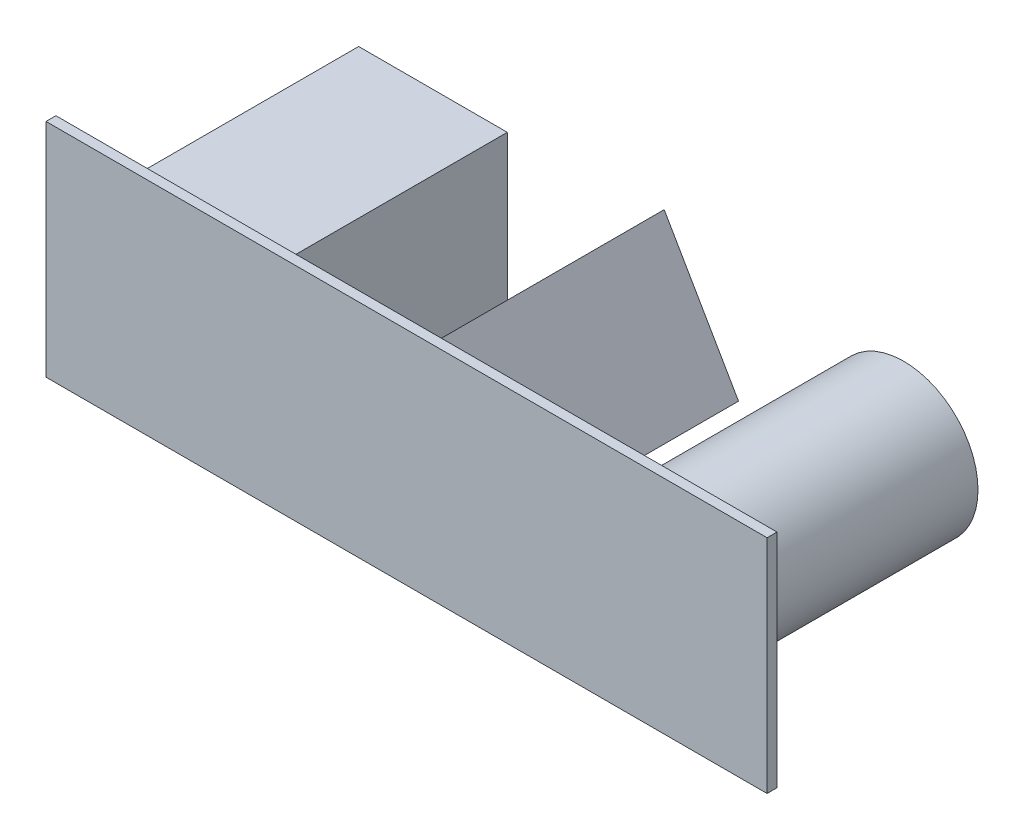
SolidWorks part; units mm, degrees
ref_plane "Front Plane" through (0, 0, 0) normal (0, 0, 1) x (1, 0, 0)
ref_plane "Top Plane" through (0, 0, 0) normal (0, 1, 0) x (1, 0, 0)
ref_plane "Right Plane" through (0, 0, 0) normal (1, 0, 0) x (0, 0, -1)
sketch "Sketch1" plane through (0, 0, 0) normal (0, 0, 1) x (1, 0, 0)
  line L0 (-122.5, 0) -> (122.5, 0) construction
  line L1 (-122.5, 60) -> (122.5, 60)
  line L2 (-122.5, 60) -> (-122.5, -60)
  line L3 (-122.5, -60) -> (122.5, -60)
  line L4 (122.5, 60) -> (122.5, -60)
  line L5 (0, 60) -> (0, -60) construction
  line L6 (-22.5, -12.9904) -> (0, 25.9808)
  line L7 (-92.5, 22.5) -> (-47.5, 22.5)
  line L8 (-92.5, 22.5) -> (-92.5, -22.5)
  line L9 (-92.5, -22.5) -> (-47.5, -22.5)
  line L10 (-47.5, 22.5) -> (-47.5, -22.5)
  line L11 (-92.5, 22.5) -> (-47.5, -22.5) construction
  line L12 (-92.5, -22.5) -> (-47.5, 22.5) construction
  line L14 (-1.3522, 0) -> (0, -1.3522)
  line L18 (0, 25.9808) -> (22.5, -12.9904)
  line L19 (22.5, -12.9904) -> (-22.5, -12.9904)
  line L20 (-22.5, -12.9904) -> (11.25, 6.4952) construction
  line L21 (22.5, -12.9904) -> (-11.25, 6.4952) construction
  line L22 (0, 25.9808) -> (0, 0) construction
  circle A0 centre (72.5, 0) radius 22.5
  point P10 (-70, 0)
  point P20 (0, 0)
  point P27 (7.7505, -5.3087)
  point P28 (0, 0)
  dimension "D2" = 50
  dimension "cylinder" = 45
  dimension "D1" = 30
  dimension "square2" = 45
  dimension "square" = 45
  dimension "triangle3" = 45
  dimension "triangle2" = 45
  dimension "triangle" = 45
extrude "Boss-Extrude1" add sketch "Sketch1" along normal blind 75
sketch "Sketch2" plane through (0, 0, 75) normal (0, 0, 1) x (1, 0, 0)
  line L5 (109.1487, -33.5279) -> (-109.1487, -33.5279)
  line L6 (109.1487, -33.5279) -> (109.1487, 33.5279)
  line L7 (109.1487, 33.5279) -> (-109.1487, 33.5279)
  line L8 (-109.1487, -33.5279) -> (-109.1487, 33.5279)
  line L9 (109.1487, -33.5279) -> (-109.1487, 33.5279) construction
  line L10 (109.1487, 33.5279) -> (-109.1487, -33.5279) construction
  point P0 (0, 0)
extrude "Boss-Extrude2" add sketch "Sketch2" along normal blind 3
